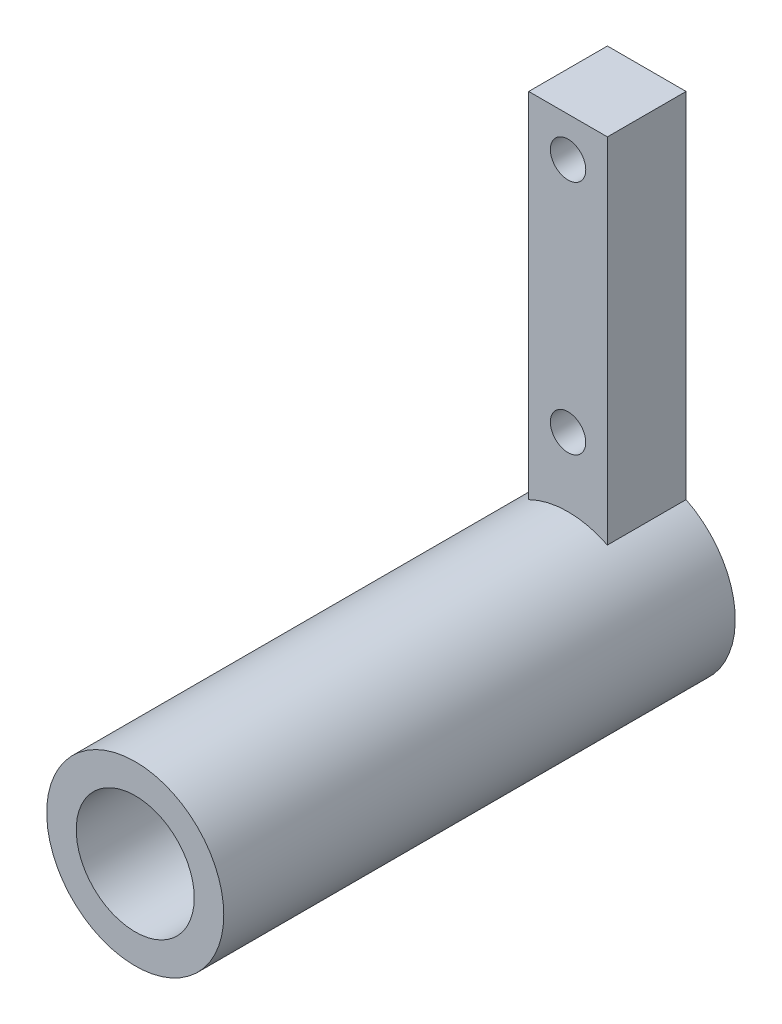
SolidWorks part; units mm, degrees
material "PW80:Mi:0:5:C1:0:1:2:Re:26:"
ref_plane "Plan1" through (0, 0, 0) normal (0, 0, 1) x (1, 0, 0)
ref_plane "Plan2" through (0, 0, 0) normal (0, 1, 0) x (1, 0, 0)
ref_plane "Plan3" through (0, 0, 0) normal (1, 0, 0) x (0, 0, -1)
sketch "Esquisse1" plane through (0, 0, 0) normal (0, 0, 1) x (1, 0, 0)
  circle A0 centre (0, 0) radius 22.5
extrude "Base-Extrusion" add sketch "Esquisse1" along normal blind 130
sketch "Esquisse2" plane through (0, 0, 0) normal (0, 1, 0) x (1, 0, 0)
  line L0 (22.5, 0) -> (-22.5, 0) construction
  line L1 (-10, 0) -> (10, 0)
  line L2 (-10, 0) -> (-10, -20)
  line L3 (-10, -20) -> (10, -20)
  line L4 (10, 0) -> (10, -20)
extrude "Boss.-Extru.1" add sketch "Esquisse2" along normal blind 110
sketch "Esquisse3" plane through (0, 0, 20) normal (0, 0, 1) x (1, 0, 0)
  circle A0 centre (0, 100) radius 4.5
  circle A1 centre (0, 40) radius 4.5
extrude "Enlèv. mat.-Extru.1" cut sketch "Esquisse3" against normal blind 20
sketch "Esquisse4" plane through (0, 0, 130) normal (0, 0, 1) x (1, 0, 0)
  circle A0 centre (0, 0) radius 15
extrude "Enlèv. mat.-Extru.2" cut sketch "Esquisse4" against normal blind 120
